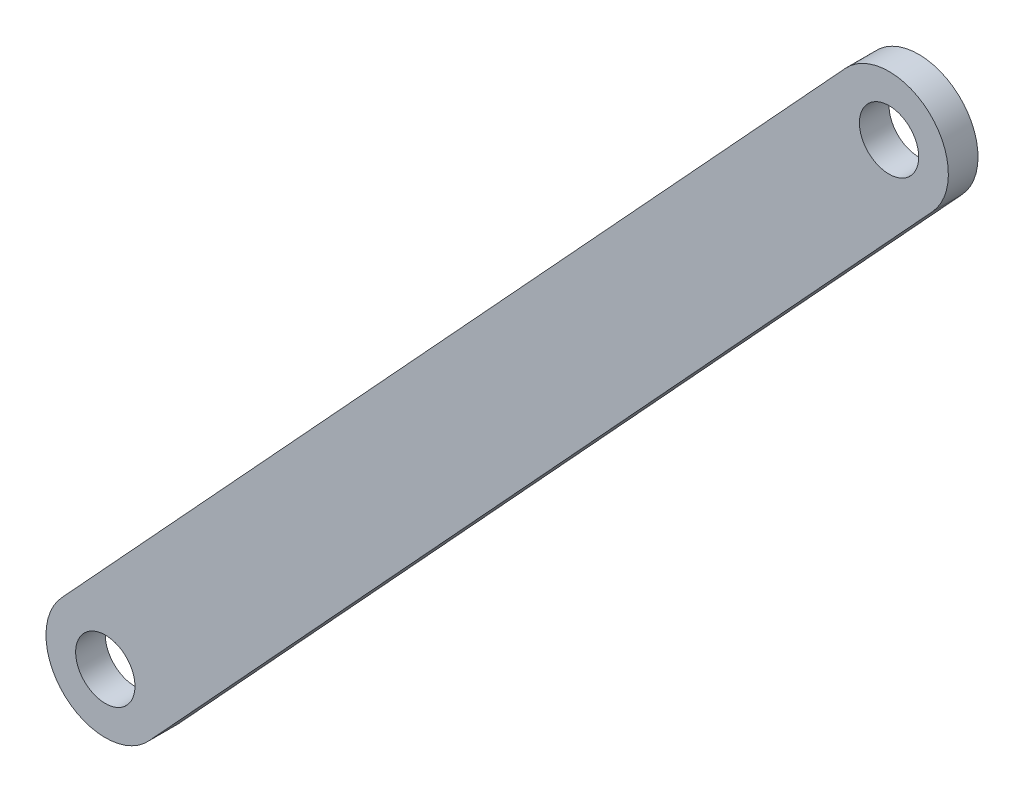
SolidWorks part; units mm, degrees
ref_plane "Front" through (0, 0, 0) normal (0, 0, 1) x (1, 0, 0)
ref_plane "Top" through (0, 0, 0) normal (0, 1, 0) x (1, 0, 0)
ref_plane "Right" through (0, 0, 0) normal (1, 0, 0) x (0, 0, -1)
sketch "Sketch1" plane through (0, 0, 0) normal (0, 0, 1) x (1, 0, 0)
  line L0 (15, 0) -> (-26.9521, -45.5152) construction
  line L1 (17.3346, -2.1518) -> (-24.6175, -47.667)
  line L2 (12.6654, 2.1518) -> (-29.2867, -43.3633)
  arc A0 (17.3346, -2.1518) -> (12.6654, 2.1518) centre (15, 0) ccw
  arc A1 (-29.2867, -43.3633) -> (-24.6175, -47.667) centre (-26.9521, -45.5152) ccw
  circle A2 centre (-26.9521, -45.5152) radius 1.5875
  circle A3 centre (15, 0) radius 1.5875
  point P4 (-5.9761, -22.7576)
  dimension "D2" = 3.175
  dimension "D1" = 6.35
extrude "Boss-Extrude1" add sketch "Sketch1" along normal blind 1.5875 from offset 1.5875
